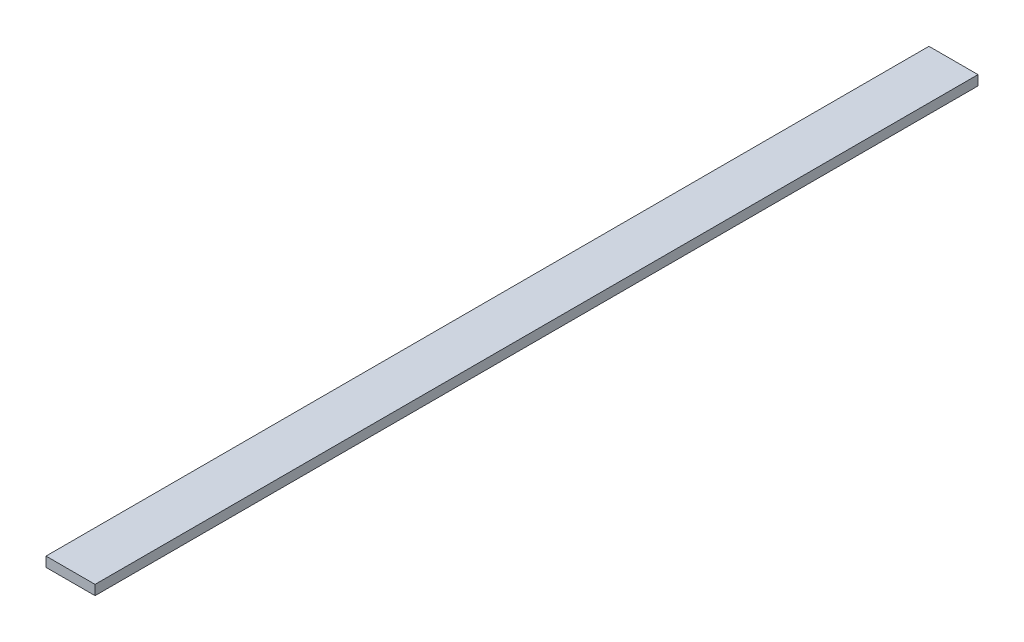
SolidWorks part; units mm, degrees
ref_plane "Plan1" through (0, 0, 0) normal (0, 0, 1) x (1, 0, 0)
ref_plane "Plan2" through (0, 0, 0) normal (0, 1, 0) x (1, 0, 0)
ref_plane "Plan3" through (0, 0, 0) normal (1, 0, 0) x (0, 0, -1)
sketch "Esquisse1" plane through (0, 0, 0) normal (0, 0, 1) x (1, 0, 0)
  line L1 (0, 0) -> (10, 0)
  line L2 (0, 0) -> (0, 2)
  line L3 (0, 2) -> (10, 2)
  line L4 (10, 0) -> (10, 2)
  dimension "D1" = 2
extrude "Base-Extrusion" add sketch "Esquisse1" along normal blind 180
